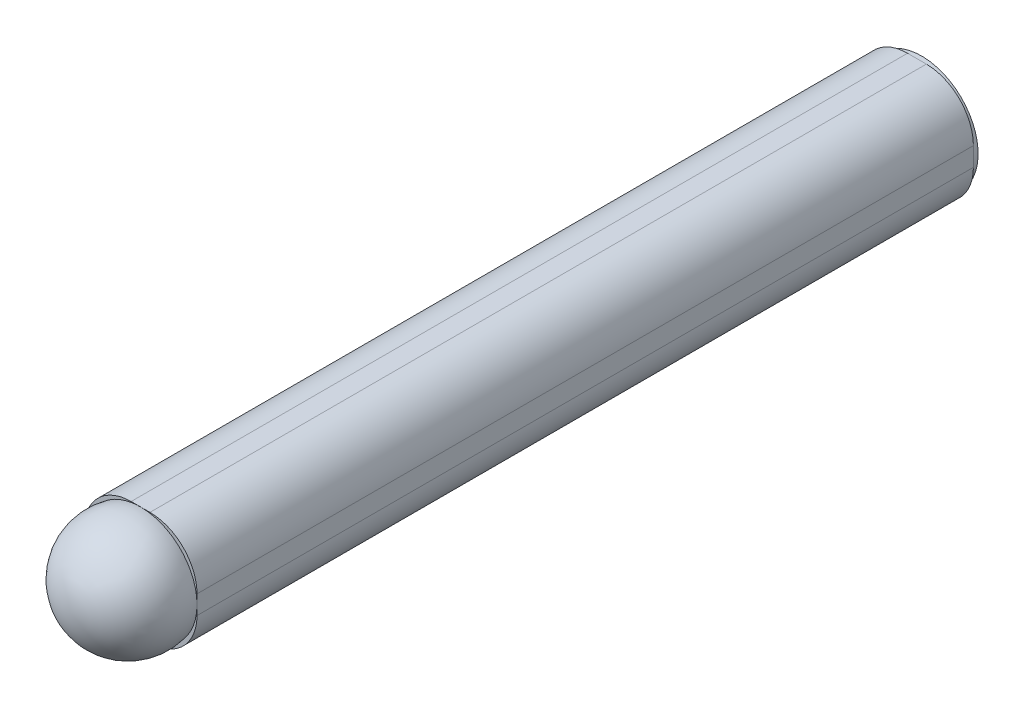
SolidWorks part; units mm, degrees
ref_plane "Front Plane" through (0, 0, 0) normal (0, 0, 1) x (1, 0, 0)
ref_plane "Top Plane" through (0, 0, 0) normal (0, 1, 0) x (1, 0, 0)
ref_plane "Right Plane" through (0, 0, 0) normal (1, 0, 0) x (0, 0, -1)
sketch "Sketch1" plane through (0, 0, 0) normal (0, 0, 1) x (1, 0, 0)
  line L1 (-12, -12) -> (12, -12)
  line L2 (-12, -12) -> (-12, 12)
  line L3 (-12, 12) -> (12, 12)
  line L4 (12, -12) -> (12, 12)
  line L5 (-12, -12) -> (12, 12) construction
  line L6 (-12, 12) -> (12, -12) construction
  point P0 (0, 0)
  dimension "D1" = 24
  dimension "D2" = 24
extrude "Boss-Extrude1" add sketch "Sketch1" along normal blind 165
ref_plane "Plane1" through (0, 0, 0) normal (0, -1, 0) x (-1, 0, 0)
sketch "Sketch3" plane through (0, 0, 0) normal (0, -1, 0) x (-1, 0, 0)
  line L0 (0, -165) -> (0, -180)
  line L1 (12, -165) -> (-12, -165) construction
  line L2 (0, -165) -> (12, -165)
  arc A0 (0, -180) -> (12, -165) centre (0, -167.7) ccw
  dimension "D1" = 15
revolve "Revolve1" add sketch "Sketch3" angle 360 about L0
fillet "Fillet1" radius 10 4 edges at (12, -12, 82.5) (12, 12, 82.5) (-12, -12, 82.5) (-12, 12, 82.5)
sketch "Sketch4" plane through (0, 0, 0) normal (0, 0, -1) x (-1, 0, 0)
  circle A0 centre (0, 0) radius 12
extrude "Boss-Extrude2" add sketch "Sketch4" along normal blind 1 contours A0
